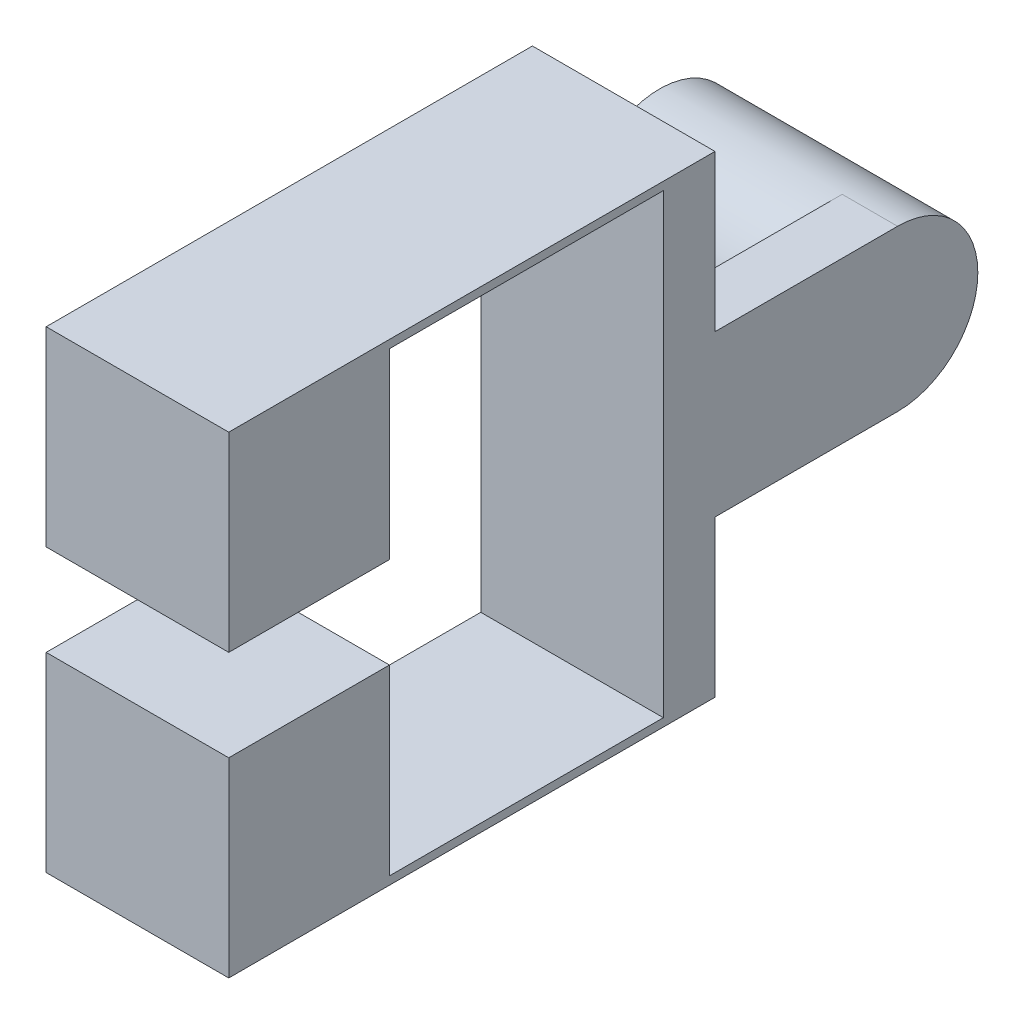
SolidWorks part; units mm, degrees
ref_plane "Front Plane" through (0, 0, 0) normal (1, 0, 0) x (0, 1, 0)
ref_plane "Top Plane" through (0, 0, 0) normal (0, 0, 1) x (0, 1, 0)
ref_plane "Right Plane" through (0, 0, 0) normal (0, 1, 0) x (-1, 0, 0)
sketch "Sketch1" plane through (0, 0, 0) normal (1, 0, 0) x (0, 1, 0)
  line L3 (0, 0) -> (0, 25.4)
  line L4 (0, 25.4) -> (22.3256, 25.4)
  line L5 (22.3256, 0) -> (22.3256, 25.4)
  arc A1 (0, 0) -> (22.3256, 0) centre (11.1628, 0) ccw
  dimension "D1" = 25.4
  dimension "D2" = 22.3256
extrude "Feature B" add sketch "Sketch1" along normal blind 7.7061
sketch "Sketch3" plane through (0, 0, 0) normal (-1, 0, 0) x (0, -1, 0)
  circle A0 centre (-11.1628, 0) radius 11.1628
extrude "Feature A" add sketch "Sketch3" along normal blind 25.4
sketch "Sketch5" plane through (7.7061, 0, 0) normal (1, 0, 0) x (0, 1, 0)
  line L0 (0, 25.4) -> (0, 0) construction
  line L1 (-21.7161, 25.4) -> (44.0417, 25.4)
  line L2 (-21.7161, 25.4) -> (-21.7161, 32.5842)
  line L3 (-21.7161, 32.5842) -> (44.0417, 32.5842)
  line L4 (44.0417, 25.4) -> (44.0417, 32.5842)
  dimension "D1" = 65.7578
  dimension "D2" = 21.7161
  dimension "D3" = 7.1842
extrude "Feature C" add sketch "Sketch5" against normal blind 25.4
sketch "Sketch6" plane through (0, 0, 32.5842) normal (0, 0, 1) x (1, 0, 0)
  line L0 (-17.6939, 44.0417) -> (-17.6939, -21.7161) construction
  line L1 (7.7061, -21.7161) -> (-17.6939, -21.7161)
  line L2 (7.7061, -21.7161) -> (7.7061, -20.5872)
  line L3 (7.7061, -20.5872) -> (-17.6939, -20.5872)
  line L4 (-17.6939, -21.7161) -> (-17.6939, -20.5872)
  line L5 (7.7061, 44.0417) -> (7.7061, -21.7161) construction
  line L6 (-17.6939, 44.0417) -> (7.7061, 44.0417)
  line L7 (-17.6939, 44.0417) -> (-17.6939, 42.9128)
  line L8 (-17.6939, 42.9128) -> (7.7061, 42.9128)
  line L9 (7.7061, 44.0417) -> (7.7061, 42.9128)
  dimension "D1" = 1.1289
  dimension "D2" = 1.1289
extrude "Feature D" add sketch "Sketch6" along normal blind 38.1
sketch "Sketch8" plane through (0, 0, 70.6842) normal (0, 0, 1) x (1, 0, 0)
  line L0 (7.7061, 42.9128) -> (7.7061, -20.5872) construction
  line L1 (-17.6939, -21.7161) -> (7.7061, -21.7161)
  line L2 (-17.6939, -21.7161) -> (-17.6939, 4.8128)
  line L3 (-17.6939, 4.8128) -> (7.7061, 4.8128)
  line L4 (7.7061, -21.7161) -> (7.7061, 4.8128)
  line L6 (-17.6939, 44.0417) -> (7.7061, 44.0417)
  line L7 (-17.6939, 44.0417) -> (-17.6939, 17.5128)
  line L8 (-17.6939, 17.5128) -> (7.7061, 17.5128)
  line L9 (7.7061, 44.0417) -> (7.7061, 17.5128)
  dimension "D1" = 26.5289
  dimension "D2" = 26.5289
extrude "Boss-Extrude5" add sketch "Sketch8" along normal blind 22.3548
equation "\"Force1\"= 1000"
equation "\"Youngs\"= 10 * 10 ^ 6"
equation "\"yield\"= 3 * 10 ^ 4"
equation "\"l\" = 1in"
equation "\"Safety\"= 4"
equation "\"Z\" = \"Safety\" * \"Force1\" * \"l\" / ( 2 * \"yield\" )"
equation "\"a\"= ( ( 4 * \"Z\" ) / pi ) ^ ( 1 / 3 )"
equation "\"stressmax\" = ( \"Force1\" * \"l\" ) / ( 2 * \"Z\" )"
equation "\"b\"= ( 2 * \"Force1\" ) / ( \"stressmax\" * 2 * \"a\" )"
equation "\"Force2\"= 500"
equation "\"h\"= 2.5"
equation "\"Zc\" = ( \"Safety\" * \"Force1\" * \"l\" ) / ( 4 * \"yield\" )"
equation "\"c\"= ( ( 6 * \"Zc\" ) / ( \"h\" ) ) ^ ( 1 / 2 )"
equation "\"i\"= 1.5"
equation "\"d\"= \"Force2\" / ( \"i\" * \"stressmax\" )"
equation "\"k\"= 1"
equation "\"Ze\"= ( ( \"Force2\" * \"l\" ) / ( 4 * \"stressmax\" ) ) ^ ( 1 / 2 )"
equation "\"e\"= ( ( 6 * \"Ze\" ) / \"l\" ) ^ ( 1 / 2 )"
equation "\"D1@Feature B\" = \"b\""
equation "\"D1@Feature A\" = \"l\""
equation "\"D2@Sketch5\"=((\"l\"*2+\"d\"*2+.5)-\"a\"*2)/2"
equation "\"D1@Sketch5\"=(\"l\"*2)+(\"d\"*2)+.5"
equation "\"D3@Sketch5\"=\"c\""
equation "\"D1@Feature C\" = \"l\""
equation "\"D1@Sketch6\"=\"d\""
equation "\"D2@Sketch6\"=\"d\""
equation "\"D1@Feature D\" = \"i\""
equation "\"D1@Sketch8\"=\"d\"+\"k\""
equation "\"D2@Sketch8\"=\"d\"+\"k\""
equation "\"D1@Boss-Extrude5\"=\"e\""
